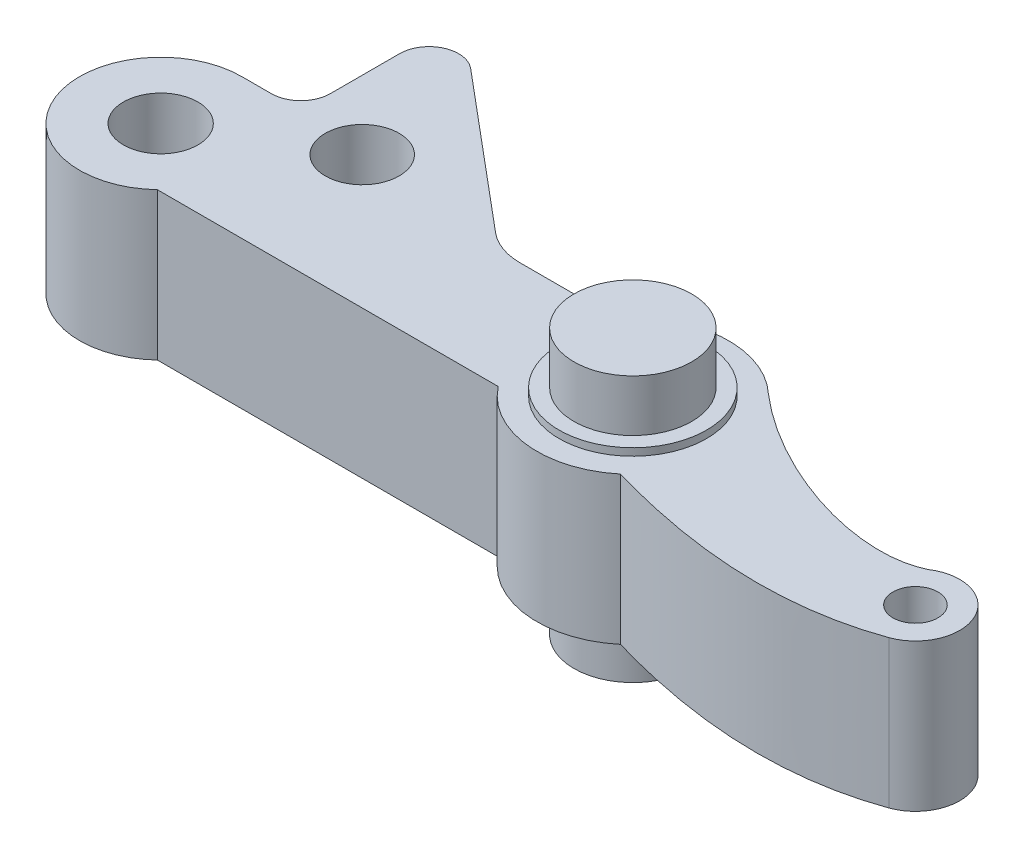
SolidWorks part; units mm, degrees
ref_plane "前视基准面" through (0, 0, 0) normal (0, 0, 1) x (1, 0, 0)
ref_plane "上视基准面" through (0, 0, 0) normal (0, 1, 0) x (1, 0, 0)
ref_plane "右视基准面" through (0, 0, 0) normal (1, 0, 0) x (0, 0, -1)
other "Configuration Table"
ref_plane "基准面1" through (0, 0, 0) normal (0, -1, 0) x (1, 0, 0)
sketch "草图1" plane through (0, 0, 0) normal (0, -1, 0) x (1, 0, 0)
  line L0 (-28, -5.5) -> (-28, -12.1939)
  line L1 (-24.7144, -13.726) -> (-13.1235, -4)
  line L2 (-13.1235, -4) -> (-5.1235, -4)
  line L3 (-5.1235, 4) -> (-28.2251, 4)
  line L4 (-32, -5.5) -> (-28, -5.5)
  arc A0 (-28, -12.1939) -> (-24.7144, -13.726) centre (-26, -12.1939) ccw
  arc A1 (-5.1235, -4) -> (4.4667, -4.7222) centre (0, 0) ccw
  arc A2 (20.4901, 0) -> (22.8497, 5.5047) centre (21.836, 2.6811) ccw
  arc A3 (4.1594, 4.9949) -> (-5.1235, 4) centre (0, 0) ccw
  arc A4 (-28.2251, 4) -> (-32, -5.5) centre (-32, 0) ccw
  ellipse E0 centre (11.3103, -6.2062) end of major axis (21.397, -0.9607) minor radius 5.0807 (20.4901, 0) -> (4.4667, -4.7222) ccw
  spline S0 degree 3 poles (4.1594, 4.9949) (11.5538, 7.1534) (17.7839, 7.3233) (22.8497, 5.5047) knots 0 0 0 0 1 1 1 1
  point P8 (11.3103, -6.2062)
  point P9 (21.397, -0.9607)
  point P10 (8.9662, -1.6986)
  point P11 (20.4901, 0)
  point P12 (4.4667, -4.7222)
  point P13 (11.7452, -0.4629)
  point P14 (10.8754, -11.9495)
  dimension "D1" = 2
  dimension "D2" = 6.5
  dimension "D3" = 3
  dimension "D4" = 6.5
  dimension "D5" = 5.5
  dimension "D6" = 3.2856
  dimension "D7" = 14.8765
  dimension "D8" = 22.8765
  dimension "D9" = 28
  dimension "D10" = 29.2236
  dimension "D11" = 32.1594
  dimension "D12" = 32.4667
  dimension "D13" = 36.9662
  dimension "D14" = 38.8754
  dimension "D15" = 39.3103
  dimension "D16" = 39.7452
  dimension "D17" = 48.4901
  dimension "D18" = 0.2251
  dimension "D19" = 4.4629
  dimension "D20" = 49.836
  dimension "D21" = 50.8497
  dimension "D22" = 15.9495
extrude "凸台-拉伸1" add sketch "草图1" against normal blind 10
ref_plane "基准面2" through (0, 0, 0) normal (0, 0, -1) x (-1, 0, 0)
sketch "草图2" plane through (0, 0, 0) normal (0, 0, -1) x (-1, 0, 0)
  line L0 (-3.99, -4) -> (0, -4)
  line L1 (0, -4) -> (0, 0)
  line L2 (0, 0) -> (-5, 0)
  line L3 (-5, 0) -> (-5, -0.5)
  line L4 (-5, -0.5) -> (-3.99, -0.5)
  line L5 (-3.99, -0.5) -> (-3.99, -4)
  line L6 (0, -4) -> (0, 0) construction
  dimension "D1" = 1.01
  dimension "D2" = 5
  dimension "D3" = 3.5
  dimension "D4" = 4
revolve "旋转1" add sketch "草图2" angle 360 about L6
sketch "草图3" plane through (0, 0, 0) normal (0, 0, 1) x (1, 0, 0)
  line L0 (3.99, 14) -> (0, 14)
  line L1 (0, 14) -> (0, 10)
  line L2 (0, 10) -> (5, 10)
  line L3 (5, 10) -> (5, 10.5)
  line L4 (5, 10.5) -> (3.99, 10.5)
  line L5 (3.99, 10.5) -> (3.99, 14)
  line L6 (0, 14) -> (0, 10) construction
  dimension "D1" = 3.99
  dimension "D2" = 5
  dimension "D3" = 0.5
  dimension "D4" = 4
revolve "旋转2" add sketch "草图3" angle 360 about L6
hole_wizard "孔1" positions "草图5" profile "草图4" legacy
sketch "草图5" plane through (0, 10, 0) normal (0, 1, 0) x (1, 0, 0)
  point P0 (21.836, -2.6811)
sketch "草图4" plane through (21.836, 10, 2.6811) normal (1, 0, 0) x (0, 0, 1)
  line L0 (0, 0) -> (0, 14)
  line L1 (0, 14) -> (1.525, 14)
  line L2 (1.525, 14) -> (1.525, 0)
  line L3 (1.525, 0) -> (0, 0)
  line L4 (0, 110) -> (0, -10) construction
  dimension "直径" = 3.05
  dimension "深度" = 14
hole_wizard "孔2" positions "草图7" profile "草图6" legacy
sketch "草图7" plane through (0, 10, 0) normal (0, 1, 0) x (1, 0, 0)
  point P0 (-23.3397, 5)
sketch "草图6" plane through (-23.3397, 10, -5) normal (1, 0, 0) x (0, 0, 1)
  line L0 (0, 0) -> (0, 14)
  line L1 (0, 14) -> (2.505, 14)
  line L2 (2.505, 14) -> (2.505, 0)
  line L3 (2.505, 0) -> (0, 0)
  line L4 (0, 110) -> (0, -10) construction
  dimension "直径" = 5.01
  dimension "深度" = 14
hole_wizard "孔3" positions "草图9" profile "草图8" legacy
sketch "草图9" plane through (0, 10, 0) normal (0, 1, 0) x (1, 0, 0)
  point P0 (-32, 0)
sketch "草图8" plane through (-32, 10, 0) normal (1, 0, 0) x (0, 0, 1)
  line L0 (0, 0) -> (0, 14)
  line L1 (0, 14) -> (2.525, 14)
  line L2 (2.525, 14) -> (2.525, 0)
  line L3 (2.525, 0) -> (0, 0)
  line L4 (0, 110) -> (0, -10) construction
  dimension "直径" = 5.05
  dimension "深度" = 14
fillet "圆角1" radius 2 1 edges at (-28, 5, -5.5)
fillet "圆角2" radius 4 1 edges at (-13.1235, 5, -4)
